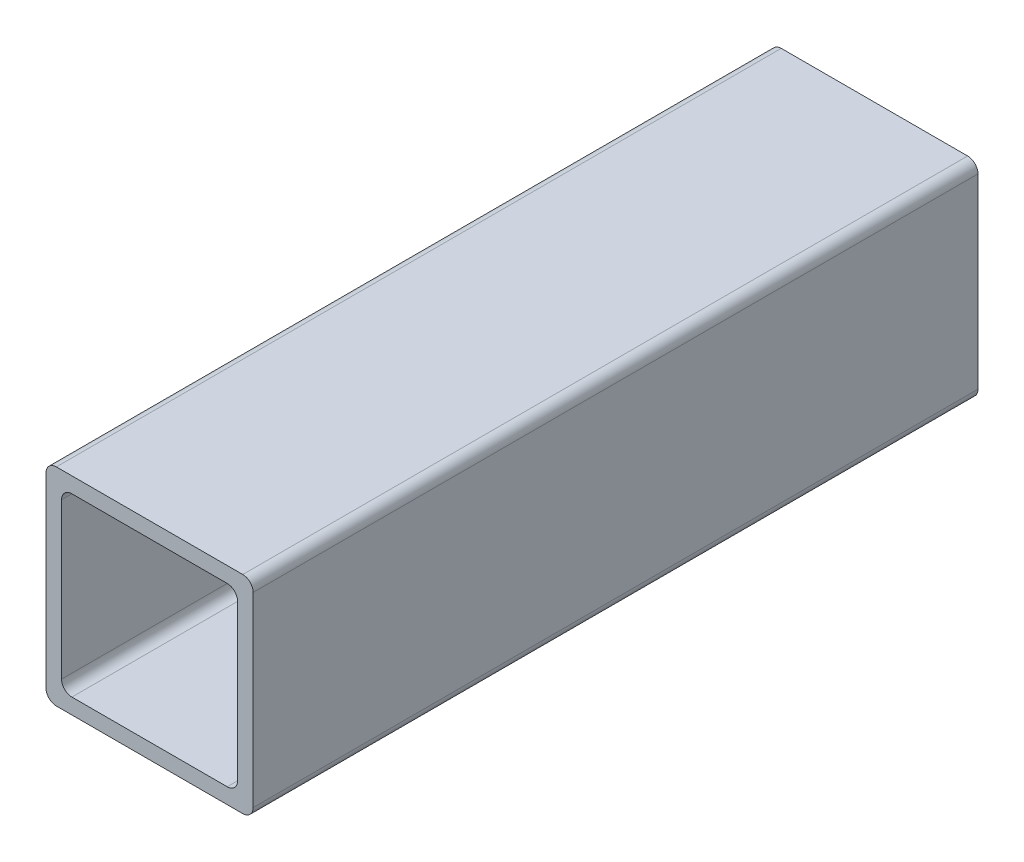
SolidWorks part; units mm, degrees
ref_plane "Front Plane" through (0, 0, 0) normal (0, 0, 1) x (1, 0, 0)
ref_plane "Top Plane" through (0, 0, 0) normal (0, 1, 0) x (1, 0, 0)
ref_plane "Right Plane" through (0, 0, 0) normal (1, 0, 0) x (0, 0, -1)
sketch "Sketch1" plane through (0, 0, 0) normal (0, 0, 1) x (1, 0, 0)
  line L1 (-20, -20) -> (20, -20)
  line L2 (-20, -20) -> (-20, 20)
  line L3 (-20, 20) -> (20, 20)
  line L4 (20, -20) -> (20, 20)
  line L5 (-20, -20) -> (20, 20) construction
  line L6 (-20, 20) -> (20, -20) construction
  point P0 (0, 0)
  dimension "D1" = 40
  dimension "D2" = 40
extrude "Boss-Extrude1" add sketch "Sketch1" along normal blind 140
sketch "Sketch2" plane through (0, 0, 140) normal (0, 0, 1) x (1, 0, 0)
  line L1 (-17, -17) -> (17, -17)
  line L2 (-17, -17) -> (-17, 17)
  line L3 (-17, 17) -> (17, 17)
  line L4 (17, -17) -> (17, 17)
  line L5 (-17, -17) -> (17, 17) construction
  line L6 (-17, 17) -> (17, -17) construction
  point P0 (0, 0)
  dimension "D1" = 34
  dimension "D2" = 34
extrude "Cut-Extrude1" cut sketch "Sketch2" against normal through all
fillet "Fillet1" radius 2 4 edges at (-20, -20, 70) (20, -20, 70) (20, 20, 70) (-20, 20, 70)
fillet "Fillet2" radius 2 4 edges at (17, -17, 70) (17, 17, 70) (-17, -17, 70) (-17, 17, 70)
